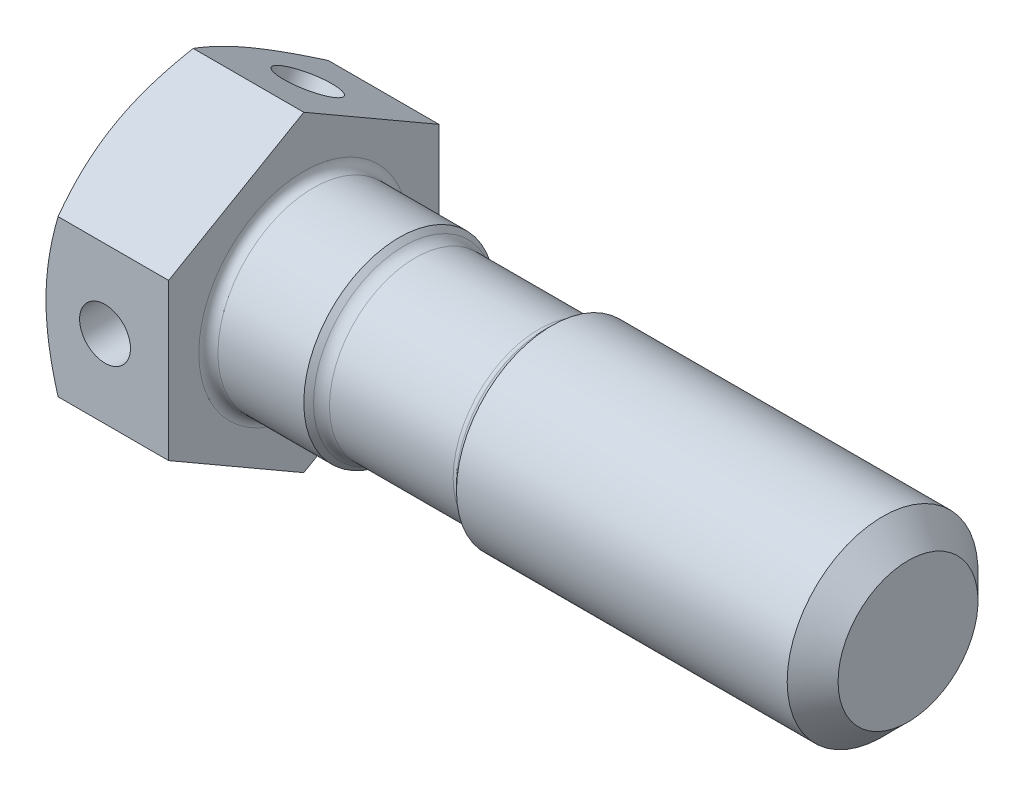
SolidWorks part; units mm, degrees
material "Простая углеродистая сталь"
ref_plane "Спереди" through (0, 0, 0) normal (0, 0, 1) x (1, 0, 0)
ref_plane "Сверху" through (0, 0, 0) normal (0, 1, 0) x (1, 0, 0)
ref_plane "Справа" through (0, 0, 0) normal (1, 0, 0) x (0, 0, -1)
sketch "Эскиз1" plane through (0, 0, 0) normal (0, 0, 1) x (1, 0, 0)
  line L0 (0, 0) -> (41.4975, 0) construction
  line L1 (0, 0) -> (0, 6)
  line L2 (0, 6) -> (6, 6)
  line L3 (6, 6) -> (6.3071, 5.6929)
  line L4 (7.0142, 5.4) -> (14.7929, 5.4)
  line L5 (15.1464, 5.5464) -> (15.6, 6)
  line L6 (15.6, 6) -> (36.4, 6)
  line L7 (38, 4.4) -> (38, 0)
  line L8 (38, 0) -> (0, 0)
  line L9 (36.4, 6) -> (38, 4.4)
  arc A0 (7.0142, 5.4) -> (6.3071, 5.6929) centre (7.0142, 6.4) cw
  arc A1 (15.1464, 5.5464) -> (14.7929, 5.4) centre (14.7929, 5.9) cw
  point P3 (38, 6)
  point P16 (15, 5.4)
  dimension "D10" = 1
  dimension "D11" = 0.5
  dimension "D1" = 12
  dimension "D2" = 10.8
  dimension "D3" = 12
  dimension "D4" = 45
  dimension "D5" = 6
  dimension "D6" = 23
  dimension "D7" = 38
  dimension "D8" = 1.6
  dimension "D9" = 45
revolve "Повернуть1" add sketch "Эскиз1" angle 360 about L0
cosmetic thread "Условное изображение резьбы1" parameters "D2"=10.072
sketch "Эскиз2" plane through (0, 0, 0) normal (-1, 0, 0) x (0, 0, 1)
  line L0 (-8.5, 0) -> (8.5, 0) construction
  line L1 (0, -9.815) -> (0, 9.815) construction
  line L3 (0, -9.815) -> (8.5, -4.9075)
  line L4 (8.5, -4.9075) -> (8.5, 4.9075)
  line L5 (8.5, 4.9075) -> (0, 9.815)
  line L6 (0, 9.815) -> (-8.5, 4.9075)
  line L7 (-8.5, 4.9075) -> (-8.5, -4.9075)
  line L8 (-8.5, -4.9075) -> (0, -9.815)
  circle A0 centre (0, 0) radius 9.815 construction
  point P6 (0, 0)
  dimension "D1" = 17
extrude "Бобышка-Вытянуть1" add sketch "Эскиз2" along normal blind 8
sketch "Эскиз3" plane through (-8, 0, 0) normal (-1, 0, 0) x (0, 0, 1)
  circle A0 centre (0, 0) radius 8
  dimension "D1" = 16
extrude "Вырез-Вытянуть1" cut sketch "Эскиз3" against normal through all draft 60 flip side to cut
fillet "Скругление1" radius 0.6 1 edges at (0, 0, 6)
sketch "Эскиз4" plane through (0, 0, 8.5) normal (0, 0, 1) x (1, 0, 0)
  line L0 (-9.9529, 0) -> (8.4534, 0) construction
  line L1 (-8, 8) -> (-8, -8) construction
  circle A0 centre (-4, 0) radius 1.6
  dimension "D1" = 3.2
  dimension "D2" = 4
extrude "Вырез-Вытянуть2" cut sketch "Эскиз4" against normal through all
sketch "Эскиз5" plane through (0, -7.3612, 4.25) normal (0, -0.866, 0.5) x (1, 0, 0)
  line L0 (-10.0003, 0) -> (5.1327, 0) construction
  line L1 (-8, 8) -> (-8, -8) construction
  circle A0 centre (-4, 0) radius 1.75
  dimension "D1" = 3.5
  dimension "D2" = 4
extrude "Вырез-Вытянуть3" cut sketch "Эскиз5" against normal through all
